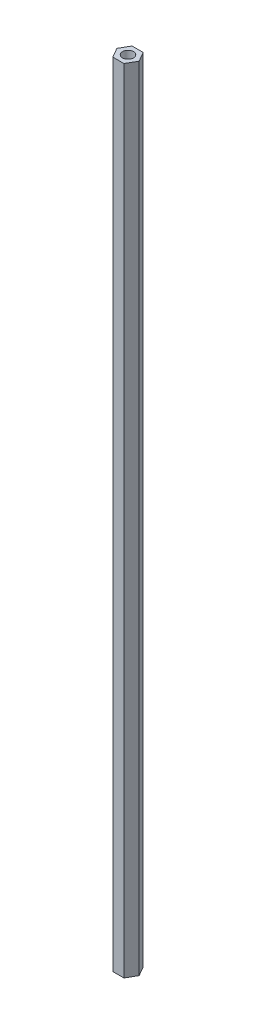
SolidWorks part; units mm, degrees
ref_plane "Front Plane" through (0, 0, 0) normal (0, 0, 1) x (1, 0, 0)
ref_plane "Top Plane" through (0, 0, 0) normal (0, 1, 0) x (1, 0, 0)
ref_plane "Right Plane" through (0, 0, 0) normal (1, 0, 0) x (0, 0, -1)
sketch "Sketch1" plane through (0, 0, 0) normal (0, 1, 0) x (1, 0, 0)
  line L1 (2.0207, 3.5) -> (-2.0207, 3.5)
  line L2 (-2.0207, 3.5) -> (-4.0415, 0)
  line L3 (-4.0415, 0) -> (-2.0207, -3.5)
  line L4 (-2.0207, -3.5) -> (2.0207, -3.5)
  line L5 (2.0207, -3.5) -> (4.0415, 0)
  line L6 (4.0415, 0) -> (2.0207, 3.5)
  circle A0 centre (0, 0) radius 3.5 construction
  circle A1 centre (0, 0) radius 2
  dimension "D1" = 7
  dimension "D2" = 4
extrude "Boss-Extrude1" add sketch "Sketch1" along normal blind 288
